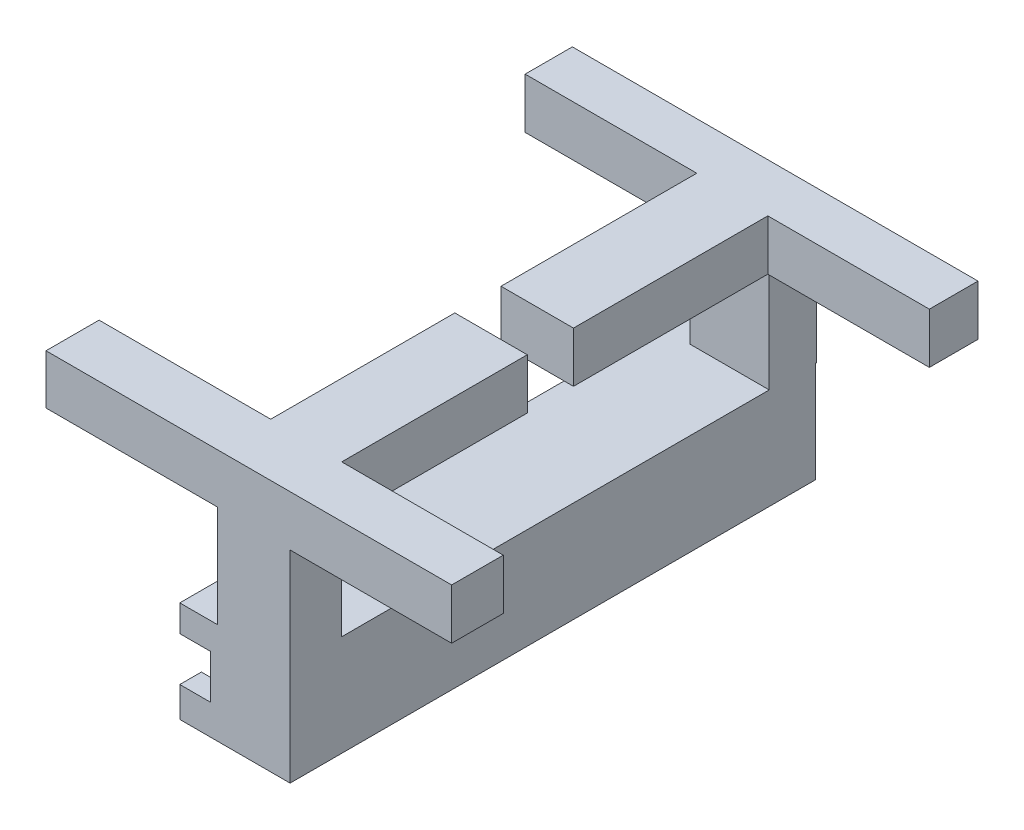
SolidWorks part; units mm, degrees
ref_plane "Front Plane" through (0, 0, 0) normal (0, 0, 1) x (1, 0, 0)
ref_plane "Top Plane" through (0, 0, 0) normal (0, 1, 0) x (1, 0, 0)
ref_plane "Right Plane" through (0, 0, 0) normal (1, 0, 0) x (0, 0, -1)
sketch "Sketch4" plane through (0, -18, 0) normal (0, 1, 0) x (1, 0, 0)
  line L1 (-349.9257, -164.1853) -> (-378.6313, -164.1853)
  line L2 (-349.9257, -164.1853) -> (-349.9257, 44.3417)
  line L3 (-349.9257, 44.3417) -> (-378.6313, 44.3417)
  line L4 (-378.6313, -164.1853) -> (-378.6313, 44.3417)
  point P4 (-380.3232, 32.0382)
  point P5 (-379.6753, 39.0449)
  point P6 (-380.0056, 41.3789)
  point P7 (-378.6313, 44.3417)
extrude "Boss-Extrude5" add sketch "Sketch4" along normal blind 20
sketch "Sketch5" plane through (0, -18, 0) normal (0, -1, 0) x (1, 0, 0)
  line L0 (-378.6313, -44.3417) -> (-378.6313, 164.1853) construction
  line L1 (-349.9257, 164.1853) -> (-378.6313, 164.1853)
  line L2 (-349.9257, 164.1853) -> (-349.9257, 143.7358)
  line L3 (-349.9257, 143.7358) -> (-378.6313, 143.7358)
  line L4 (-378.6313, 164.1853) -> (-378.6313, 143.7358)
  line L5 (-304.155, 143.7358) -> (-431.155, 143.7358) construction
  line L6 (-349.9257, 164.1853) -> (-349.9257, -44.3417) construction
  line L7 (-349.9257, -25.635) -> (-381.371, -25.635)
  line L8 (-349.9257, -25.635) -> (-349.9257, -44.3417)
  line L9 (-349.9257, -44.3417) -> (-381.371, -44.3417)
  line L10 (-381.371, -25.635) -> (-381.371, -44.3417)
  line L11 (-349.9257, -44.3417) -> (-378.6313, -44.3417) construction
  point P17 (-349.9257, -25.635)
  point P18 (-349.9257, 164.1853)
extrude "Boss-Extrude6" add sketch "Sketch5" along normal blind 40
sketch "Sketch6" plane through (0, -58, 0) normal (0, -1, 0) x (1, 0, 0)
  line L1 (-349.9257, 164.1853) -> (-381.371, 164.1853)
  line L2 (-349.9257, 164.1853) -> (-349.9257, -43.8945)
  line L3 (-349.9257, -43.8945) -> (-381.371, -43.8945)
  line L4 (-381.371, 164.1853) -> (-381.371, -43.8945)
  point P6 (-349.9257, -205.3526)
  point P7 (-349.9257, -205.3526)
extrude "Boss-Extrude7" add sketch "Sketch6" along normal blind 40
sketch "Sketch7" plane through (-378.6313, 0, 0) normal (-1, 0, 0) x (0, 0, 1)
  line L6 (-44.3417, 2) -> (164.1853, 2) construction
  line L7 (51.9233, 2) -> (70.2233, 2)
  line L8 (51.9233, 2) -> (51.9233, -18)
  line L9 (51.9233, -18) -> (70.2233, -18)
  line L10 (70.2233, 2) -> (70.2233, -18)
  line L11 (-25.635, -18) -> (143.7358, -18) construction
  dimension "D1" = 18.3
extrude "Cut-Extrude1" cut sketch "Sketch7" against normal up to surface (28.7056 mm away) up to face at (-349.9257, -51.3333, 25.3164)
sketch "Sketch8" plane through (-378.6313, 0, 0) normal (-1, 0, 0) x (0, 0, 1)
  line L10 (164.1853, -98) -> (164.1853, -58) construction
  line L11 (-43.8945, -58) -> (164.1853, -58)
  line L12 (-43.8945, -58) -> (-43.8945, -68.5629)
  line L13 (-43.8945, -68.5629) -> (164.1853, -68.5629)
  line L14 (164.1853, -58) -> (164.1853, -68.5629)
  line L15 (-43.8945, -98) -> (-43.8945, -58) construction
  line L16 (-43.8945, -86.0065) -> (164.1853, -86.0065)
  line L17 (-43.8945, -86.0065) -> (-43.8945, -98)
  line L18 (-43.8945, -98) -> (164.1853, -98)
  line L19 (164.1853, -86.0065) -> (164.1853, -98)
extrude "Boss-Extrude8" add sketch "Sketch8" along normal blind 15
ref_plane "Plane1" through (-393.6313, -58, 164.1853) normal (0, 0, 1) x (1, 0, 0)
sketch "Sketch11" plane through (-393.6313, 0, 0) normal (-1, 0, 0) x (0, 0, 1)
  line L1 (155.629, -94.2387) -> (135.629, -94.2387)
  line L2 (155.629, -94.2387) -> (155.629, -62.2387)
  line L3 (155.629, -62.2387) -> (135.629, -62.2387)
  line L4 (135.629, -94.2387) -> (135.629, -62.2387)
  line L5 (-33.8893, -62.2924) -> (-13.8893, -62.2924)
  line L6 (-33.8893, -62.2924) -> (-33.8893, -94.2924)
  line L7 (-33.8893, -94.2924) -> (-13.8893, -94.2924)
  line L8 (-13.8893, -62.2924) -> (-13.8893, -94.2924)
  dimension "D1" = 20
  dimension "D2" = 32
  dimension "D3" = 20
  dimension "D4" = 32
extrude "Cut-Extrude2" cut sketch "Sketch11" against normal blind 39 contours L2 L1 L4 L3 | L6 L5 L8 L7
sketch "Sketch12" plane through (-378.6313, 0, 0) normal (-1, 0, 0) x (0, 0, 1)
  line L0 (164.1853, 2) -> (164.1853, -58) construction
  line L1 (164.1853, -17.6565) -> (143.1623, -17.6565)
  line L2 (164.1853, -17.6565) -> (164.1853, 2)
  line L3 (164.1853, 2) -> (143.1623, 2)
  line L4 (143.1623, -17.6565) -> (143.1623, 2)
  line L5 (70.2233, 2) -> (164.1853, 2) construction
  line L7 (-25.635, -18) -> (-44.3417, -18)
  line L8 (-25.635, -18) -> (-25.635, 2)
  line L9 (-25.635, 2) -> (-44.3417, 2)
  line L10 (-44.3417, -18) -> (-44.3417, 2)
extrude "Boss-Extrude10" add sketch "Sketch12" along normal blind 68
sketch "Sketch13" plane through (-349.9257, 0, 0) normal (1, 0, 0) x (0, 0, -1)
  line L0 (-51.9233, 2) -> (44.3417, 2) construction
  line L1 (44.3417, -18) -> (25.0728, -18)
  line L2 (44.3417, -18) -> (44.3417, 2)
  line L3 (44.3417, 2) -> (25.0728, 2)
  line L4 (25.0728, -18) -> (25.0728, 2)
  line L5 (-143.7358, -58) -> (-143.7358, -18) construction
  line L6 (-143.7358, -18) -> (-164.1853, -18)
  line L7 (-143.7358, -18) -> (-143.7358, 2)
  line L8 (-143.7358, 2) -> (-164.1853, 2)
  line L9 (-164.1853, -18) -> (-164.1853, 2)
  line L10 (-164.1853, 2) -> (-164.1853, -98) construction
extrude "Boss-Extrude11" add sketch "Sketch13" along normal blind 64
